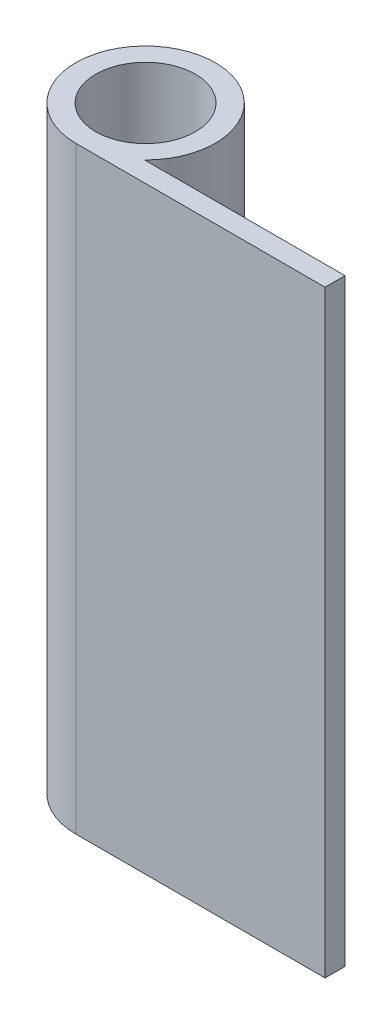
SolidWorks part; units mm, degrees
ref_plane "Front Plane" through (0, 0, 0) normal (0, 0, 1) x (1, 0, 0)
ref_plane "Top Plane" through (0, 0, 0) normal (0, 1, 0) x (1, 0, 0)
ref_plane "Right Plane" through (0, 0, 0) normal (1, 0, 0) x (0, 0, -1)
sketch "Sketch1" plane through (0, 0, 0) normal (0, 1, 0) x (1, 0, 0)
  line L0 (0, -7) -> (25, -7)
  line L1 (25, -7) -> (25, -5)
  line L2 (25, -5) -> (4.899, -5)
  arc A0 (4.899, -5) -> (0, -7) centre (0, 0) ccw
  circle A1 centre (0, 0) radius 5
  dimension "D1" = 10
  dimension "D2" = 14
  dimension "D3" = 25
extrude "Boss-Extrude1" add sketch "Sketch1" along normal mid plane 60
